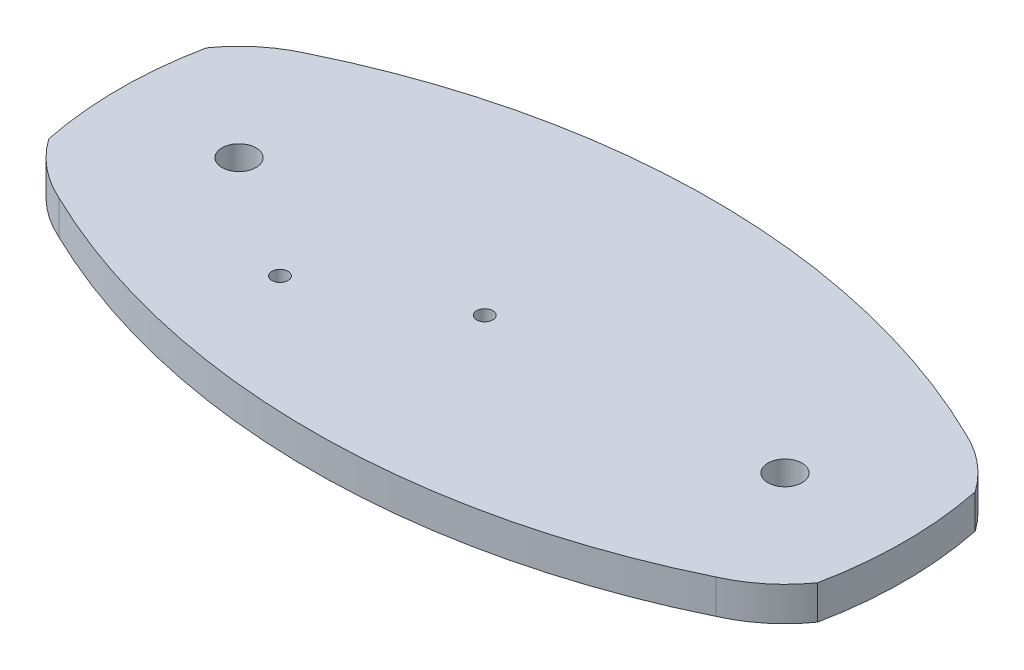
SolidWorks part; units mm, degrees
ref_plane "Front Plane" through (0, 0, 0) normal (0, 0, 1) x (1, 0, 0)
ref_plane "Top Plane" through (0, 0, 0) normal (0, 1, 0) x (1, 0, 0)
ref_plane "Right Plane" through (0, 0, 0) normal (1, 0, 0) x (0, 0, -1)
sketch "Sketch1" plane through (0, 0, 0) normal (0, 1, 0) x (1, 0, 0)
  circle A0 centre (0, 0) radius 73.025
  dimension "D1" = 146.05
extrude "Boss-Extrude1" add sketch "Sketch1" along normal blind 6.35
sketch "Sketch2" plane through (0, 6.35, 0) normal (0, 1, 0) x (1, 0, 0)
  line L0 (0, -55) -> (0, 55) construction
  line L1 (-50.8, -25.4) -> (50.8, -25.4)
  line L3 (-50.8, 25.4) -> (50.8, 25.4)
  line L4 (71.842, -14.2265) -> (71.842, 14.2265)
  line L5 (-63.0049, -22.2756) -> (63.0049, 22.2756) construction
  line L6 (-63.0049, 22.2756) -> (63.0049, -22.2756) construction
  circle A1 centre (-50.8, 0) radius 3.175
  circle A2 centre (50.8, 0) radius 3.175
  circle A3 centre (-50.8, 0) radius 25.4
  circle A4 centre (50.8, 0) radius 25.4
  arc A6 (-63.0049, 22.2756) -> (63.0049, 22.2756) centre (0, -102.4099) cw
  arc A7 (-63.0049, -22.2756) -> (63.0049, -22.2756) centre (0, 102.4099) ccw
  point P0 (0, 0)
  dimension "D2" = 6.35
  dimension "D3" = 50.8
extrude "Cut-Extrude2" cut sketch "Sketch2" against normal blind 6.35
sketch "Sketch3" plane through (0, 6.35, 0) normal (0, 1, 0) x (1, 0, 0)
  line L0 (-2.54, -2.54) -> (-2.54, -15.24)
  line L1 (-2.54, -15.24) -> (-27.94, -15.24)
  dimension "D1" = 12.7
  dimension "D2" = 25.4
  dimension "D3" = 2.54
  dimension "D4" = 2.54
hole_wizard "Ø3.0mm Dowel Hole1" positions "Sketch4" profile "Sketch5" hole size "Ø3.0" standard "ANSI Metric" end condition through all
sketch "Sketch4" plane through (0, 6.35, 0) normal (0, 1, 0) x (1, 0, 0)
  point P0 (-27.94, -15.24)
  point P3 (-2.54, -2.54)
sketch "Sketch5" plane through (-27.94, 6.35, 15.24) normal (1, 0, 0) x (0, 0, 1)
  line L0 (0, 0) -> (0, 6.35)
  line L1 (0, 6.35) -> (1.5, 6.35)
  line L2 (1.5, 6.35) -> (1.5, 0)
  line L5 (1.5, 0) -> (0, 0)
  line L11 (0, -6.35) -> (0, 107.95) construction
  dimension "Thru Hole Dia." = 3
  dimension "Thru Hole Depth" = 6.35
